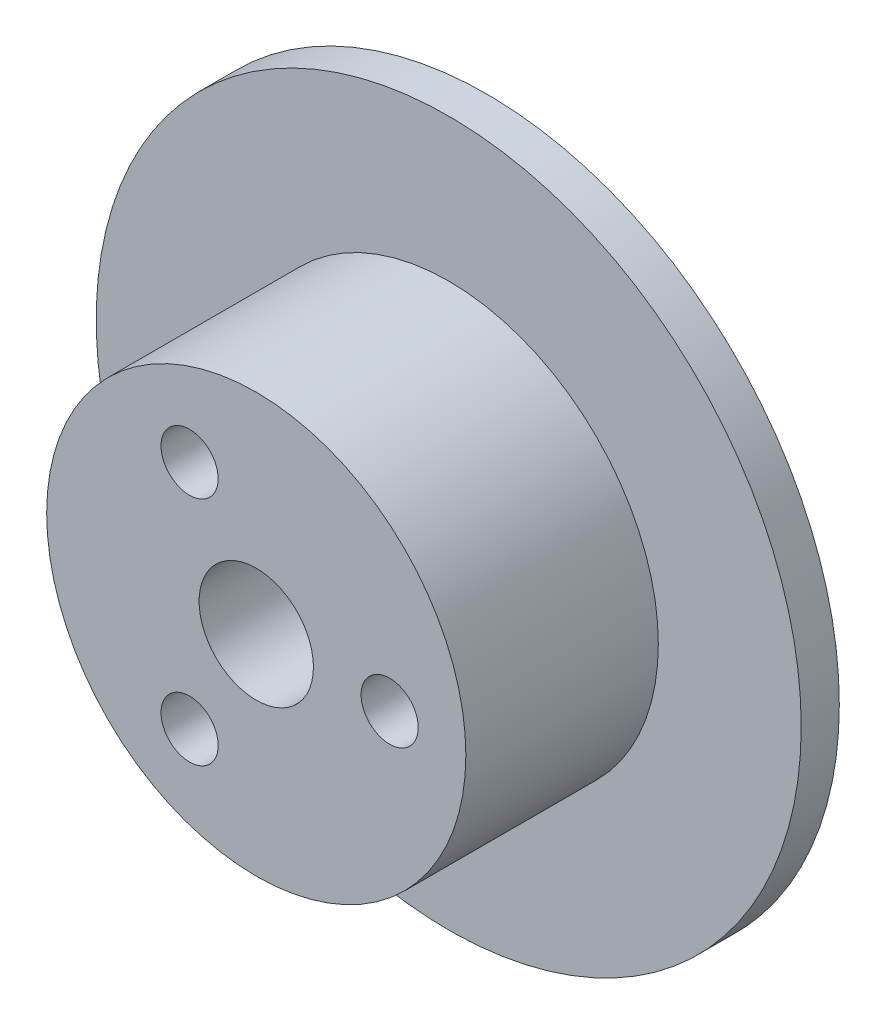
SolidWorks part; units mm, degrees
ref_plane "Front Plane" through (0, 0, 0) normal (0, 0, 1) x (1, 0, 0)
ref_plane "Top Plane" through (0, 0, 0) normal (0, 1, 0) x (1, 0, 0)
ref_plane "Right Plane" through (0, 0, 0) normal (1, 0, 0) x (0, 0, -1)
sketch "Sketch1" plane through (0, 0, 0) normal (0, 0, 1) x (1, 0, 0)
  circle A0 centre (0, 0) radius 18.5
  dimension "D1" = 37
extrude "Boss-Extrude1" add sketch "Sketch1" along normal blind 3
sketch "Sketch2" plane through (0, 0, 3) normal (0, 0, 1) x (1, 0, 0)
  circle A0 centre (0, 0) radius 11
  dimension "D1" = 22
extrude "Boss-Extrude2" add sketch "Sketch2" along normal blind 2.5 contours A0
sketch "Sketch4" plane through (0, 0, 0) normal (0, 0, -1) x (-1, 0, 0)
  circle A0 centre (0, 0) radius 3.05
  dimension "D1" = 6.1
extrude "Cut-Extrude1" cut sketch "Sketch4" against normal through all
sketch "Sketch7" plane through (0, 0, 5.5) normal (0, 0, 1) x (1, 0, 0)
  circle A0 centre (0, 0) radius 3
  circle A1 centre (0, 0) radius 11
  dimension "D1" = 22
extrude "Boss-Extrude3" add sketch "Sketch7" along normal blind 6.6
sketch "Sketch9" plane through (0, 0, 12.1) normal (0, 0, 1) x (1, 0, 0)
  line L0 (0, 0) -> (7, 0) construction
  circle A0 centre (7, 0) radius 1.5
  circle A1 centre (-3.5, -6.0622) radius 1.5
  circle A2 centre (-3.5, 6.0622) radius 1.5
  dimension "D2" = 3
  dimension "D1" = 7
  dimension "D3" = 3
extrude "Cut-Extrude4" cut sketch "Sketch9" against normal through all
sketch "Sketch10" plane through (0, 0, 3) normal (0, 0, 1) x (1, 0, 0)
  circle A0 centre (0, 0) radius 11
  circle A1 centre (0, 0) radius 18.5
extrude "Cut-Extrude5" cut sketch "Sketch10" against normal blind 1
